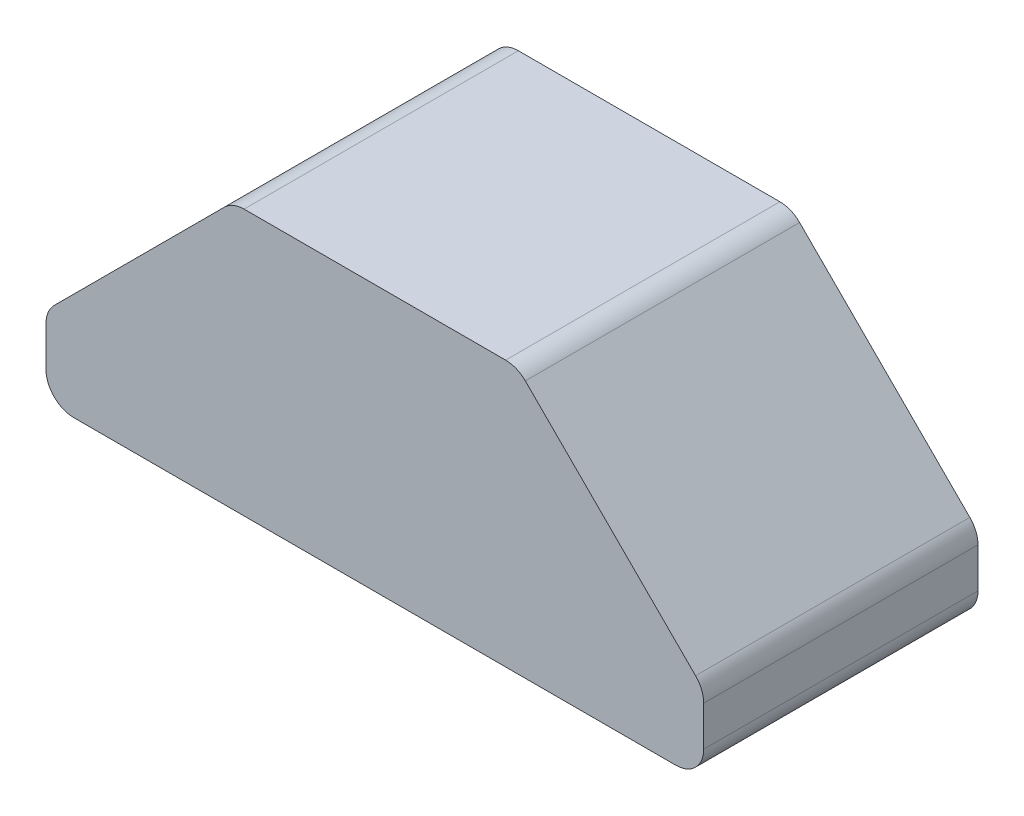
SolidWorks part; units mm, degrees
ref_plane "Přední rovina" through (0, 0, 0) normal (0, 0, 1) x (1, 0, 0)
ref_plane "Horní rovina" through (0, 0, 0) normal (0, 1, 0) x (1, 0, 0)
ref_plane "Pravá rovina" through (0, 0, 0) normal (1, 0, 0) x (0, 0, -1)
sketch "Skica1" plane through (0, 0, 0) normal (0, 0, 1) x (1, 0, 0)
  line L0 (17.6623, -11.4711) -> (11.3863, -11.4711)
  line L100 (11.3863, -11.4711) -> (9.0373, -11.4711)
  line L101 (8.5293, -10.9631) -> (8.5293, -10.2371)
  line L102 (8.6781, -9.8779) -> (11.7812, -6.7748)
  line L103 (12.1404, -6.6261) -> (16.9082, -6.6261)
  line L104 (17.2674, -6.7748) -> (20.3705, -9.8779)
  line L105 (20.5193, -10.2371) -> (20.5193, -10.9631)
  line L106 (20.0113, -11.4711) -> (17.6623, -11.4711)
  arc A101 (8.5293, -10.9631) -> (9.0373, -11.4711) centre (9.0373, -10.9631) ccw
  arc A102 (8.6781, -9.8779) -> (8.5293, -10.2371) centre (9.0373, -10.2371) ccw
  arc A103 (12.1404, -6.6261) -> (11.7812, -6.7748) centre (12.1404, -7.1341) ccw
  arc A104 (17.2674, -6.7748) -> (16.9082, -6.6261) centre (16.9082, -7.1341) ccw
  arc A105 (20.5193, -10.2371) -> (20.3705, -9.8779) centre (20.0113, -10.2371) ccw
  arc A106 (20.0113, -11.4711) -> (20.5193, -10.9631) centre (20.0113, -10.9631) ccw
extrude "Přidat vysunutím1" add sketch "Skica1" against normal blind 5
